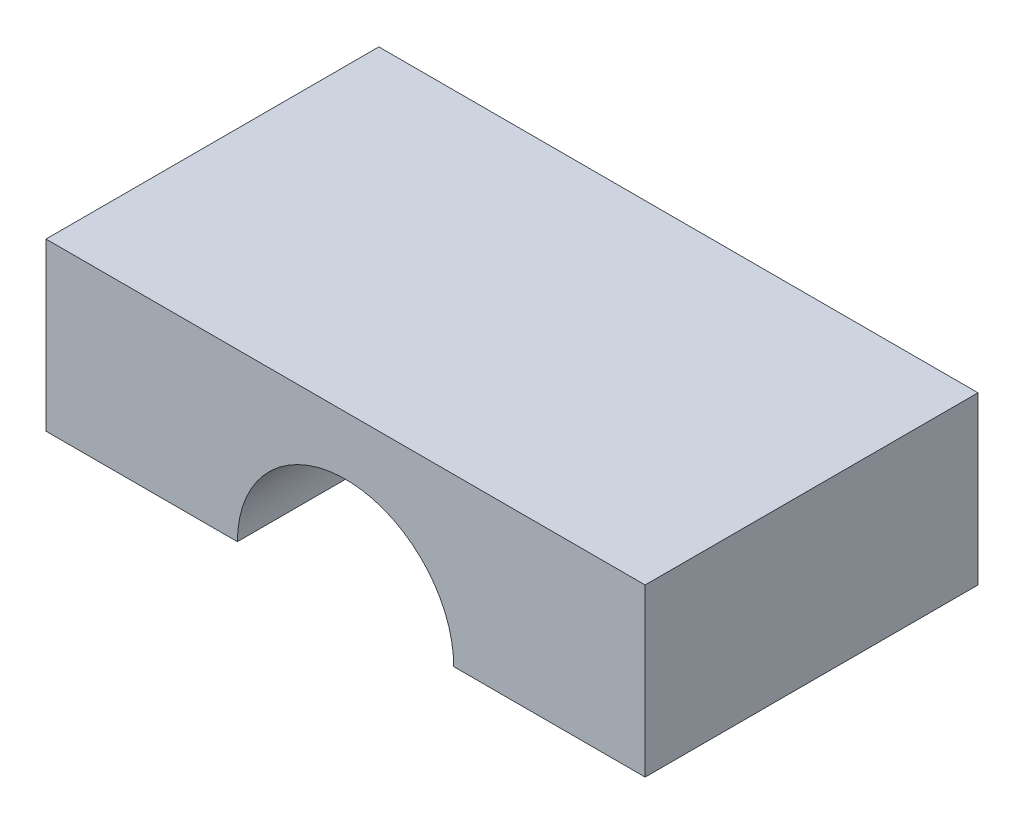
SolidWorks part; units mm, degrees
ref_plane "Front Plane" through (0, 0, 0) normal (0, 0, 1) x (1, 0, 0)
ref_plane "Top Plane" through (0, 0, 0) normal (0, 1, 0) x (1, 0, 0)
ref_plane "Right Plane" through (0, 0, 0) normal (1, 0, 0) x (0, 0, -1)
sketch "Sketch1" plane through (0, 0, 0) normal (0, 0, 1) x (1, 0, 0)
  line L0 (0, 0) -> (0, 5) construction
  line L1 (3.25, 0) -> (9, 0)
  line L2 (9, 0) -> (9, 5)
  line L3 (9, 5) -> (-9, 5)
  line L4 (-9, 0) -> (-9, 5)
  line L5 (-3.25, 0) -> (-9, 0)
  arc A0 (3.25, 0) -> (-3.25, 0) centre (0, 0) ccw
  dimension "D3" = 3.25
  dimension "D1" = 18
  dimension "D2" = 5
extrude "Boss-Extrude1" add sketch "Sketch1" along normal blind 10
